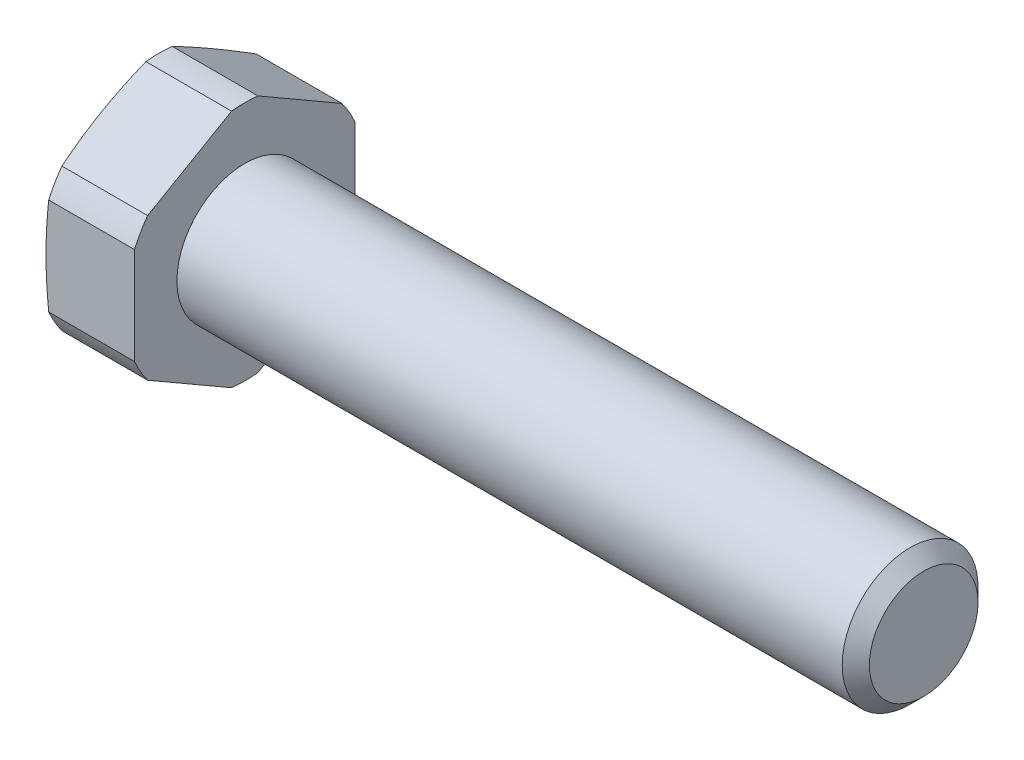
SolidWorks part; units mm, degrees
material "AISI 1020"
ref_plane "Спереди" through (0, 0, 0) normal (0, 0, 1) x (1, 0, 0)
ref_plane "Сверху" through (0, 0, 0) normal (0, 1, 0) x (1, 0, 0)
ref_plane "Справа" through (0, 0, 0) normal (1, 0, 0) x (0, 0, -1)
sketch "Эскиз1" plane through (0, 0, 0) normal (0, 0, 1) x (1, 0, 0)
  line L0 (-1000, 0) -> (49000, 0) construction
  line L1 (-5.3, 0) -> (-5.3, 6.175)
  line L2 (-5.3, 6.175) -> (-5.0521, 7.1)
  line L3 (-5.0521, 7.1) -> (0, 7.1)
  line L4 (0, 7.1) -> (0, 4)
  line L5 (0, 4) -> (39.2, 4)
  line L6 (40, 3.2) -> (40, 0)
  line L7 (40, 4) -> (40.625, 5.0825) construction
  line L8 (40.625, 5.0825) -> (41.25, 4) construction
  line L9 (41.25, 4) -> (40, 4) construction
  line L10 (40.625, 5.0825) -> (40.625, 4) construction
  line L11 (40.625, 5.0825) -> (18.625, 5.0825) construction
  line L12 (39.2, 4) -> (40, 3.2)
  line L13 (40, 4) -> (39.6, 3.6) construction
  line L14 (-5.3, 6.175) -> (-18.3, 6.175) construction
  line L15 (-5.3, 0) -> (40, 0)
  dimension "l_" = 40
  dimension "D2" = 15
revolve "Повернуть1" add sketch "Эскиз1" angle 360 about L0
cosmetic thread "Условное изображение резьбы1" parameters "D1"=22, "D2"=5.8349
sketch "Эскиз2" plane through (-5.3, 0, 0) normal (-1, 0, 0) x (0, 0, 1)
  line L1 (0, 7.5056) -> (-6.5, 3.7528)
  line L2 (-6.5, 3.7528) -> (-6.5, -3.7528)
  line L3 (-6.5, -3.7528) -> (0, -7.5056)
  line L4 (0, -7.5056) -> (6.5, -3.7528)
  line L5 (6.5, -3.7528) -> (6.5, 3.7528)
  line L6 (6.5, 3.7528) -> (0, 7.5056)
  circle A0 centre (0, 0) radius 6.5 construction
extrude "Вырез-Вытянуть1" cut sketch "Эскиз2" against normal up to surface (45.3 mm away) flip side to cut up to face at (40, 0, 3.2)
equation "\"D1@Эскиз1\"=\"_d_@Эскиз1\"/10"
equation "\"D@Эскиз1\"=\"S_@Эскиз1\"*0.95"
equation "\"D1@Эскиз2\"=\"S_@Эскиз1\""
equation "\"D1@Условное изображение резьбы1\"=\"b_@Эскиз1\""
equation "\"D2@Условное изображение резьбы1\"=\"_d_@Эскиз1\"-\"dr@Эскиз1\"*2"
